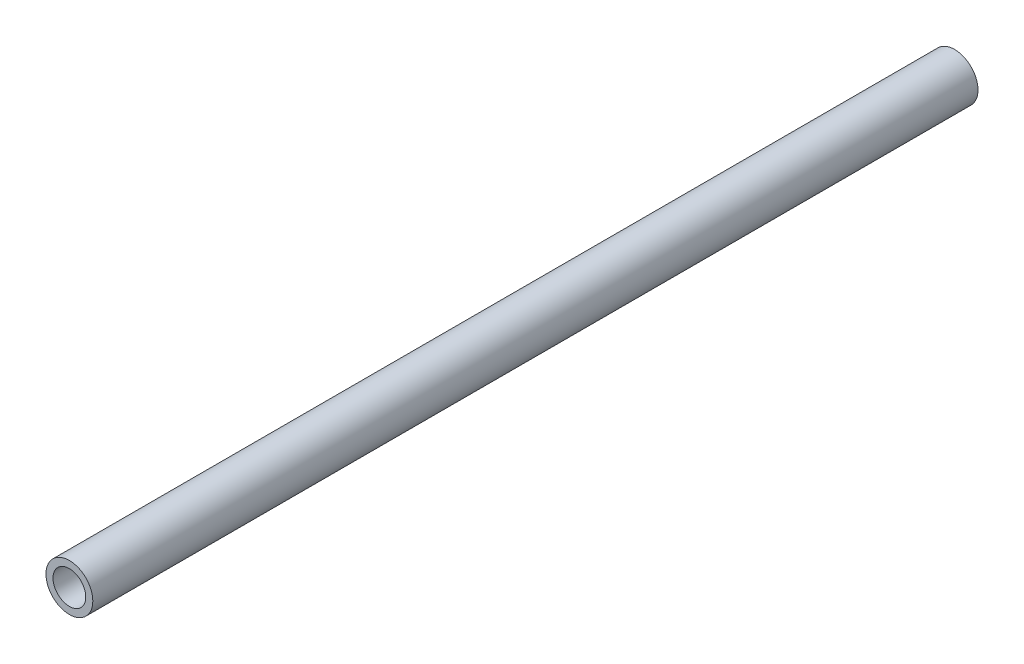
SolidWorks part; units mm, degrees
ref_plane "Front Plane" through (0, 0, 0) normal (1, 0, 0) x (0, 1, 0)
ref_plane "Top Plane" through (0, 0, 0) normal (0, 0, 1) x (0, 1, 0)
ref_plane "Right Plane" through (0, 0, 0) normal (0, 1, 0) x (-1, 0, 0)
sketch "Sketch1" plane through (0, 0, 0) normal (0, 0, 1) x (0, 1, 0)
  circle A0 centre (0, 0) radius 15.875
  circle A1 centre (0, 0) radius 11.1
  dimension "D1" = 31.75
  dimension "D2" = 22.2
extrude "Boss-Extrude1" add sketch "Sketch1" along normal blind 600
equation "\"OD\"= 1.25in"
equation "\"ID\"= 22.2"
equation "\"D1@Sketch1\"=\"OD\""
equation "\"D2@Sketch1\"=\"ID\""
equation "\"L\" = 600mm"
equation "\"D1@Boss-Extrude1\"=\"L\""
